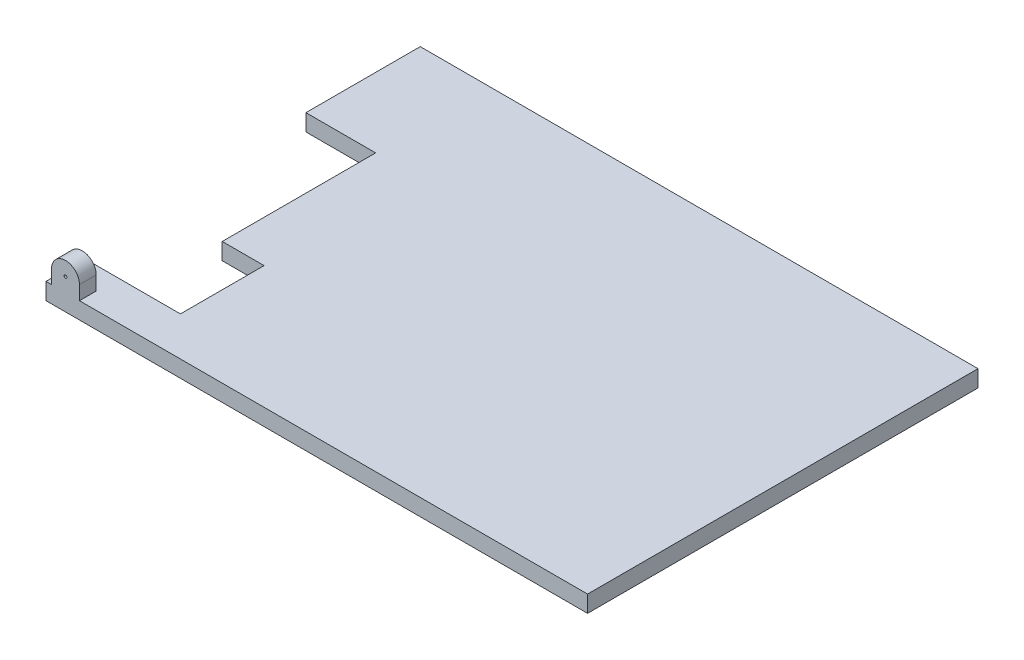
SolidWorks part; units mm, degrees
material "Acrilico TEC"
ref_plane "Front Plane" through (0, 0, 0) normal (0, 0, 1) x (1, 0, 0)
ref_plane "Top Plane" through (0, 0, 0) normal (0, 1, 0) x (1, 0, 0)
ref_plane "Right Plane" through (0, 0, 0) normal (1, 0, 0) x (0, 0, -1)
sketch "Sketch1" plane through (0, 0, 0) normal (0, 1, 0) x (1, 0, 0)
  line L0 (5.8044, 4.7967) -> (5.8044, 10.7967)
  line L1 (5.8044, 4.7967) -> (200, 4.7967)
  line L2 (0, 103.7967) -> (0, 144.7967)
  line L3 (0, 144.7967) -> (200, 144.7967)
  line L4 (200, 4.7967) -> (200, 144.7967)
  line L7 (18.8044, 18.7967) -> (25, 18.7967)
  line L8 (25, 48.7967) -> (25, 103.7967)
  line L9 (25, 103.7967) -> (0, 103.7967)
  line L10 (25, 18.7967) -> (40, 18.7967)
  line L11 (40, 18.7967) -> (40, 48.7967)
  line L12 (40, 48.7967) -> (25, 48.7967)
  line L13 (5.8044, 10.7967) -> (5.8044, 18.7967)
  line L14 (5.8044, 18.7967) -> (18.8044, 18.7967)
  dimension "D1" = 6
  dimension "D2" = 140
  dimension "D3" = 200
  dimension "D4" = 13
  dimension "D5" = 25
  dimension "D6" = 85
  dimension "D8" = 15
  dimension "D9" = 30
  dimension "D10" = 15
  dimension "D11" = 6.1956
extrude "Boss-Extrude1" add sketch "Sketch1" along normal blind 6
sketch "Sketch2" plane through (0, 0, -4.7967) normal (0, 0, 1) x (1, 0, 0)
  line L0 (5.8044, 6) -> (200, 6) construction
  line L1 (5.8044, 6) -> (5.8044, 0) construction
  line L2 (7.8044, 6) -> (17.8044, 6)
  line L3 (7.8044, 6) -> (7.8044, 11)
  line L5 (17.8044, 6) -> (17.8044, 11)
  arc A0 (17.8044, 11) -> (7.8044, 11) centre (12.8044, 11) ccw
  circle A1 centre (12.8044, 11) radius 0.5
  dimension "D3" = 1
  dimension "D4" = 5
  dimension "D1" = 5
  dimension "D2" = 10
  dimension "D5" = 2
extrude "Boss-Extrude2" add sketch "Sketch2" against normal blind 6
